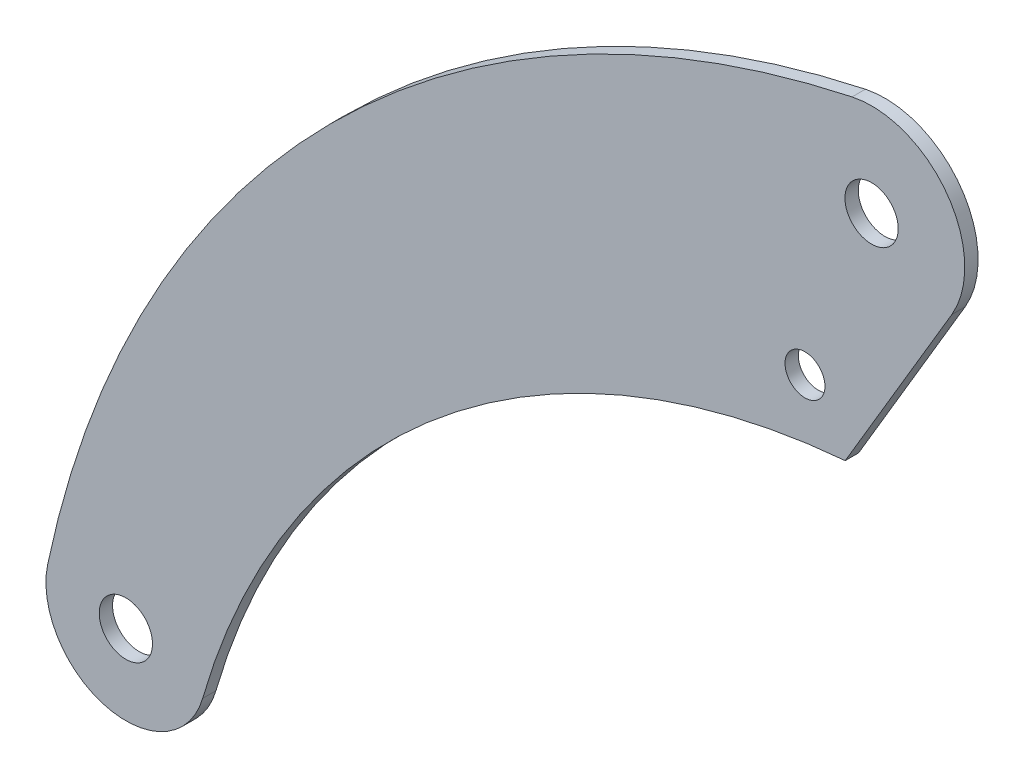
SolidWorks part; units mm, degrees
ref_plane "Front Plane" through (0, 0, 0) normal (0, 0, 1) x (1, 0, 0)
ref_plane "Top Plane" through (0, 0, 0) normal (0, 1, 0) x (1, 0, 0)
ref_plane "Right Plane" through (0, 0, 0) normal (1, 0, 0) x (0, 0, -1)
sketch "Sketch1" plane through (0, 0, 0) normal (0, 0, 1) x (1, 0, 0)
  line L0 (60.2204, -35.6862) -> (-19.7796, -170.6862)
  circle A0 centre (0, 0) radius 20
  circle A1 centre (-50, -130) radius 15
  circle A2 centre (-560, -550) radius 20
  arc A3 (-618.7157, -537.6524) -> (-502.3419, -566.5995) centre (-560, -550) ccw
  arc A4 (-14.6346, 68.4531) -> (60.2204, -35.6862) centre (0, 0) cw
  arc A5 (-19.7796, -170.6862) -> (-502.3419, -566.5995) centre (26.1907, -718.7616) ccw
  arc A6 (-14.6346, 68.4531) -> (-618.7157, -537.6524) centre (149.4818, -699.1997) ccw
  point P14 (-584.855, -480.0884)
  dimension "D1" = 40
  dimension "D2" = 30
  dimension "D3" = 40
  dimension "D8" = 60
  dimension "D9" = 70
  dimension "D12" = 550
  dimension "D13" = 785
  dimension "D4" = 50
  dimension "D5" = 130
  dimension "D6" = 560
  dimension "D7" = 550
  dimension "D10" = 135
  dimension "D11" = 80
extrude "Boss-Extrude1" add sketch "Sketch1" along normal mid plane 10
